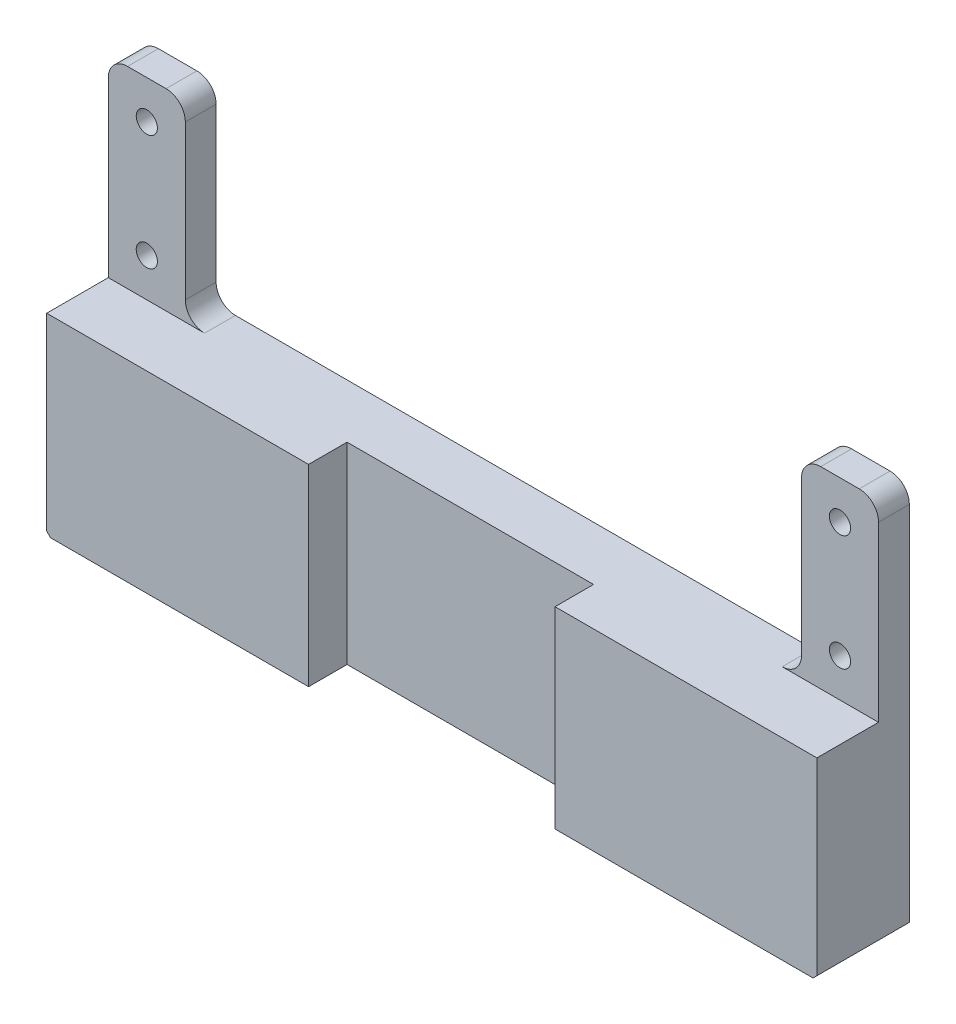
SolidWorks part; units mm, degrees
material "PE High Density"
ref_plane "Front Plane" through (0, 0, 0) normal (0, 0, 1) x (1, 0, 0)
ref_plane "Top Plane" through (0, 0, 0) normal (0, 1, 0) x (1, 0, 0)
ref_plane "Right Plane" through (0, 0, 0) normal (1, 0, 0) x (0, 0, -1)
sketch "Sketch1" plane through (0, 0, 0) normal (0, 1, 0) x (1, 0, 0)
  line L0 (-100, 8) -> (100, 8)
  line L1 (100, 8) -> (100, -16)
  line L2 (100, -16) -> (32, -16)
  line L3 (32, -16) -> (32, -6)
  line L4 (32, -6) -> (-32, -6)
  line L5 (-32, -6) -> (-32, -16)
  line L6 (-32, -16) -> (-100, -16)
  line L9 (-100, -16) -> (-100, 8)
  line L10 (0, -14.3) -> (0, 14.3) construction
  line L11 (-100, 0) -> (100, 0) construction
  point P2 (0, -6)
  point P9 (0, 0)
  dimension "D1" = 200
  dimension "D2" = 64
  dimension "D3" = 16
  dimension "D4" = 10
  dimension "D7" = 8
extrude "Boss-Extrude1" add sketch "Sketch1" against normal blind 50
sketch "Sketch2" plane through (0, 0, 0) normal (0, 1, 0) x (1, 0, 0)
  line L0 (-100, 0) -> (100, 0) construction
  line L1 (-100, 8) -> (-80, 8)
  line L2 (-100, 8) -> (-100, 0)
  line L3 (-100, 0) -> (-80, 0)
  line L4 (-80, 8) -> (-80, 0)
  line L6 (100, 8) -> (80, 8)
  line L7 (100, 8) -> (100, 0)
  line L8 (100, 0) -> (80, 0)
  line L9 (80, 8) -> (80, 0)
  dimension "D1" = 160
extrude "Boss-Extrude2" add sketch "Sketch2" along normal blind 50
hole_wizard "M5 Clearance Hole1" positions "Sketch3" profile "Sketch4" hole size "M5" standard "ANSI Metric" end condition up to next
sketch "Sketch3" plane through (0, 0, -8) normal (0, 0, -1) x (-1, 0, 0)
  line L1 (-90, 40) -> (90, 40)
  line L2 (-90, 40) -> (-90, 10)
  line L3 (-90, 10) -> (90, 10)
  line L4 (90, 40) -> (90, 10)
  line L5 (0, 13.2) -> (0, -13.2) construction
  point P1 (-90, 40)
  point P2 (90, 10)
  point P213 (-90, 10)
  point P214 (90, 40)
  point P215 (0, 10)
  dimension "D1" = 180
  dimension "D2" = 10
  dimension "D3" = 30
sketch "Sketch4" plane through (90, 40, -8) normal (1, 0, 0) x (0, 1, 0)
  line L0 (0, 0) -> (0, 8)
  line L1 (0, 8) -> (2.75, 8)
  line L2 (2.75, 8) -> (2.75, 0)
  line L5 (2.75, 0) -> (0, 0)
  line L11 (0, -6.35) -> (0, 107.95) construction
  dimension "Thru Hole Dia." = 5.5
  dimension "Thru Hole Depth" = 8
fillet "Fillet1" radius 5 6 edges at (100, 50, -4) (80, 50, -4) (-80, 50, -4) (-100, 50, -4) (80, 0, -4) (-80, 0, -4)
chamfer "Chamfer1" distance 1 2 edges at (100, -50, 4) (-100, -50, 4)
